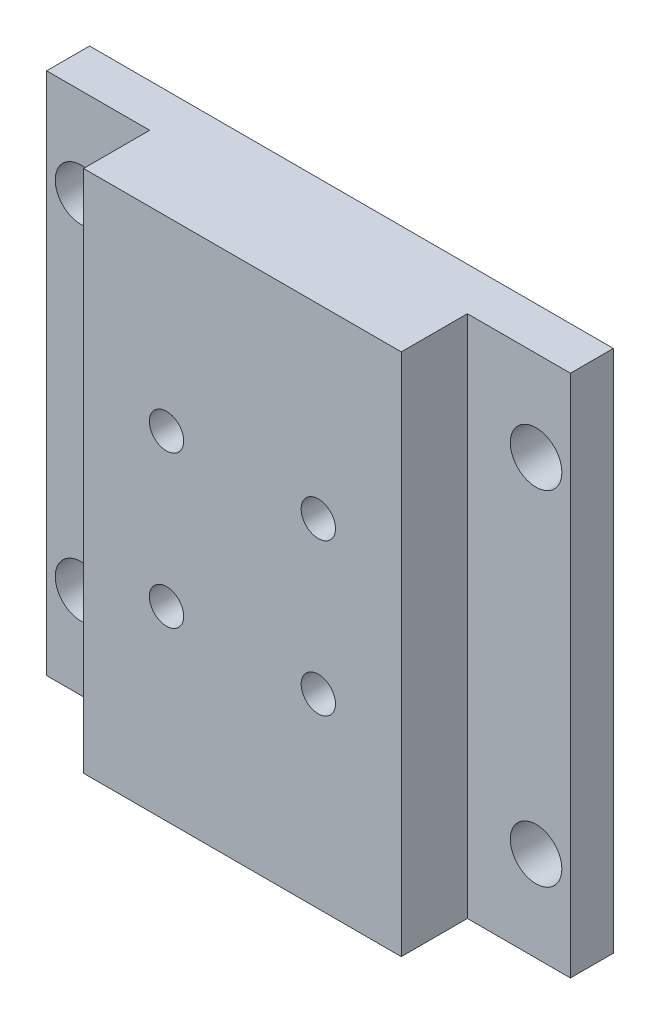
SolidWorks part; units mm, degrees
material "6061 Alloy"
ref_plane "Front Plane" through (0, 0, 0) normal (0, 0, 1) x (1, 0, 0)
ref_plane "Top Plane" through (0, 0, 0) normal (0, 1, 0) x (1, 0, 0)
ref_plane "Right Plane" through (0, 0, 0) normal (1, 0, 0) x (0, 0, -1)
sketch "Sketch1" plane through (0, 0, 0) normal (0, 0, 1) x (1, 0, 0)
  line L1 (-30.5, 30.5) -> (30.5, 30.5)
  line L2 (-30.5, 30.5) -> (-30.5, -30.5)
  line L3 (-30.5, -30.5) -> (30.5, -30.5)
  line L4 (30.5, 30.5) -> (30.5, -30.5)
  line L5 (-30.5, 30.5) -> (30.5, -30.5) construction
  line L6 (-30.5, -30.5) -> (30.5, 30.5) construction
  point P1 (0, 0)
  dimension "D1" = 61
extrude "Boss-Extrude1" add sketch "Sketch1" against normal blind 12.7
sketch "Sketch2" plane through (0, 0, 0) normal (0, 0, 1) x (1, 0, 0)
  line L1 (-8.8388, 8.8388) -> (8.8388, 8.8388) construction
  line L2 (-8.8388, 8.8388) -> (-8.8388, -8.8388) construction
  line L3 (-8.8388, -8.8388) -> (8.8388, -8.8388) construction
  line L4 (8.8388, 8.8388) -> (8.8388, -8.8388) construction
  line L5 (-8.8388, 8.8388) -> (8.8388, -8.8388) construction
  line L6 (-8.8388, -8.8388) -> (8.8388, 8.8388) construction
  circle A0 centre (0, 0) radius 12.5 construction
  circle A1 centre (8.8388, 8.8388) radius 2
  circle A2 centre (-8.8388, 8.8388) radius 2
  circle A3 centre (-8.8388, -8.8388) radius 2
  circle A4 centre (8.8388, -8.8388) radius 2
  dimension "D1" = 25
  dimension "D2" = 4
extrude "Cut-Extrude1" cut sketch "Sketch2" against normal through all
sketch "Sketch3" plane through (0, 0, 0) normal (0, 0, 1) x (1, 0, 0)
  line L0 (0, 30.5) -> (0, -30.5) construction
  line L1 (30.5, 30.5) -> (-30.5, 30.5) construction
  line L2 (-30.5, -30.5) -> (30.5, -30.5) construction
  line L3 (30.5, -30.5) -> (30.5, 30.5) construction
  line L4 (-30.5, 0) -> (30.5, 0) construction
  line L5 (-30.5, 30.5) -> (-30.5, -30.5) construction
  circle A0 centre (26.5, 20) radius 3
  circle A1 centre (26.5, -20) radius 3
  circle A2 centre (-26.5, 20) radius 3
  circle A3 centre (-26.5, -20) radius 3
  dimension "D1" = 6
  dimension "D2" = 4
  dimension "D3" = 10.5
extrude "Cut-Extrude2" cut sketch "Sketch3" against normal through all
sketch "Sketch4" plane through (0, 0, 0) normal (0, 0, 1) x (1, 0, 0)
  line L0 (-30.5, 30.5) -> (-18.5, 30.5)
  line L1 (30.5, 30.5) -> (-30.5, 30.5) construction
  line L2 (-18.5, 30.5) -> (-18.5, -30.5)
  line L3 (-30.5, -30.5) -> (30.5, -30.5) construction
  line L4 (-18.5, -30.5) -> (-30.5, -30.5)
  line L5 (-30.5, -30.5) -> (-30.5, 30.5)
  line L6 (0, 30.5) -> (0, -30.5) construction
  line L7 (30.5, -30.5) -> (30.5, 30.5)
  line L8 (18.5, -30.5) -> (30.5, -30.5)
  line L9 (18.5, 30.5) -> (18.5, -30.5)
  line L10 (30.5, 30.5) -> (18.5, 30.5)
  circle A0 centre (0, 0) radius 16 construction
  dimension "D1" = 32
  dimension "D2" = 12
extrude "Cut-Extrude3" cut sketch "Sketch4" against normal offset from surface (7.7 mm away) 5 up to face at (29.5, -20, -12.7)
